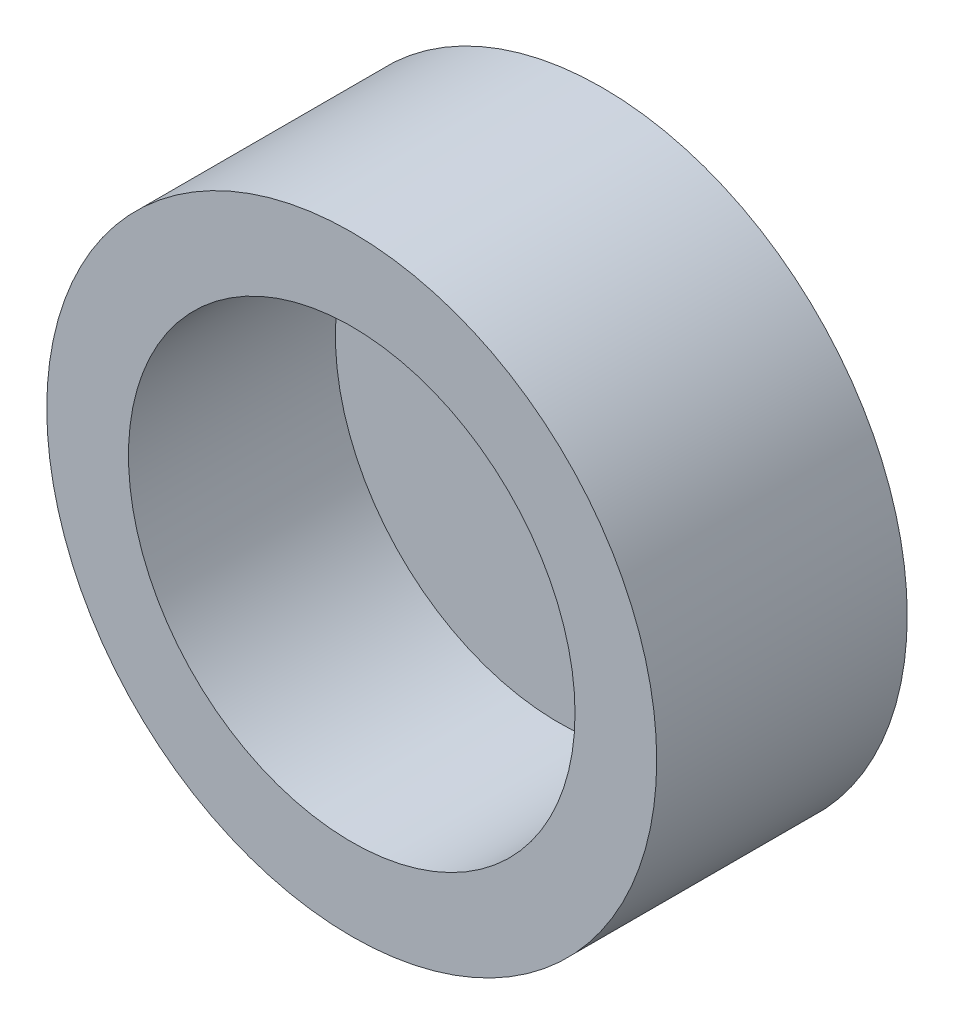
SolidWorks part; units mm, degrees
ref_plane "Alzado" through (0, 0, 0) normal (0, 0, 1) x (1, 0, 0)
ref_plane "Planta" through (0, 0, 0) normal (0, 1, 0) x (1, 0, 0)
ref_plane "Vista lateral" through (0, 0, 0) normal (1, 0, 0) x (0, 0, -1)
sketch "Croquis1" plane through (0, 0, 0) normal (0, 0, 1) x (1, 0, 0)
  circle A0 centre (0, 0) radius 56
  dimension "D1" = 112
extrude "Saliente-Extruir1" add sketch "Croquis1" along normal mid plane 46
sketch "Croquis2" plane through (0, 0, 23) normal (0, 0, 1) x (1, 0, 0)
  circle A0 centre (0, 0) radius 41
  dimension "D1" = 82
extrude "Cortar-Extruir1" cut sketch "Croquis2" against normal blind 38
